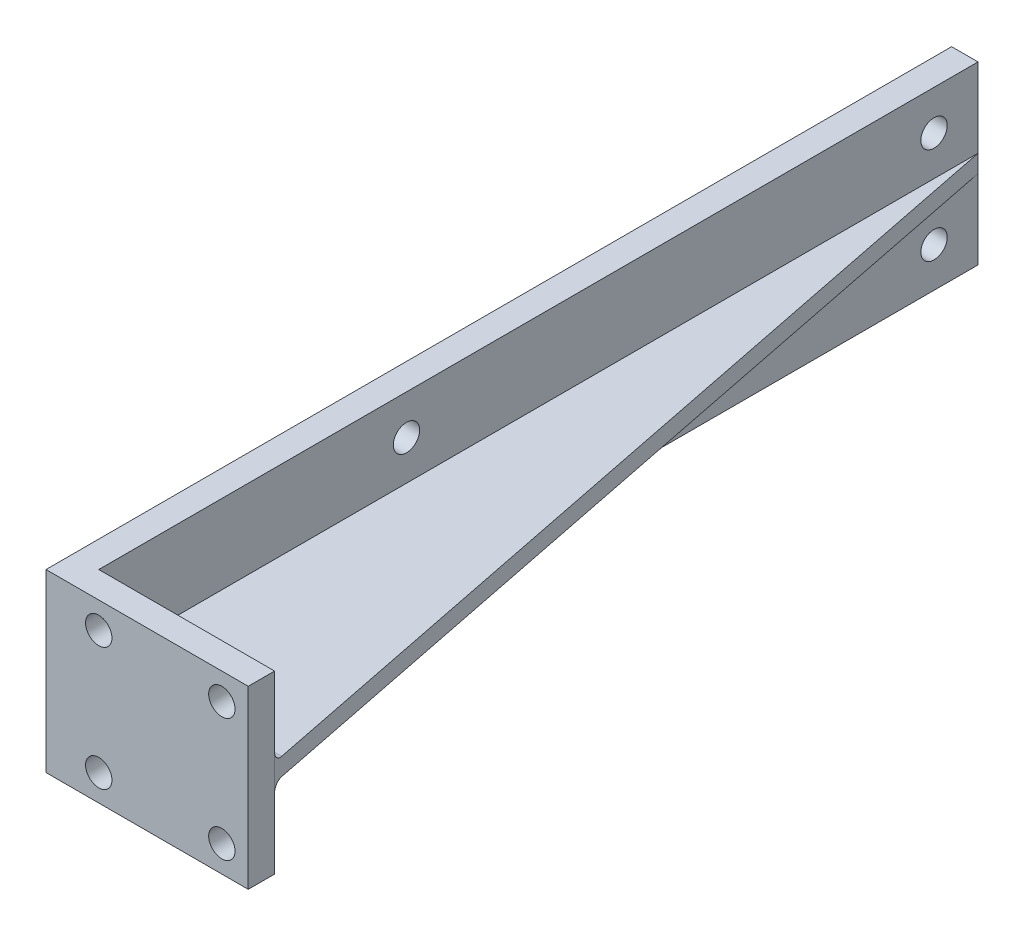
SolidWorks part; units mm, degrees
material "6061 合金"
ref_plane "前视基准面" through (0, 0, 0) normal (0, 0, 1) x (1, 0, 0)
ref_plane "上视基准面" through (0, 0, 0) normal (0, 1, 0) x (1, 0, 0)
ref_plane "右视基准面" through (0, 0, 0) normal (1, 0, 0) x (0, 0, -1)
sketch "草图1" plane through (0, 0, 0) normal (0, 1, 0) x (1, 0, 0)
  line L0 (0, 100) -> (0, 0)
  line L1 (0, 0) -> (20, 0)
  line L2 (20, 0) -> (0, 100)
  dimension "D1" = 100
  dimension "D2" = 20
extrude "凸台-拉伸1" add sketch "草图1" along normal blind 2
ref_plane "基准面1" through (0, 1, 0) normal (0, -1, 0) x (-1, 0, 0)
sketch "草图2" plane through (0, 1, 0) normal (0, -1, 0) x (-1, 0, 0)
  line L0 (-20, 0) -> (-20, -3)
  line L1 (-20, -3) -> (3, -3)
  line L2 (0, 100) -> (3, 100)
  line L3 (3, 100) -> (3, -3)
  line L4 (-20, 0) -> (0, 0)
  line L5 (0, 0) -> (0, 100)
  dimension "D1" = 3
  dimension "D2" = 3
extrude "凸台-拉伸2" add sketch "草图2" along normal blind 10 and the other way blind 10
sketch "草图3" plane through (0, 0, 0) normal (1, 0, 0) x (0, 0, -1)
  line L0 (100, 6.5) -> (0, 6.5) construction
  line L1 (100, 11) -> (100, 2) construction
  line L2 (0, 11) -> (0, 2) construction
  line L3 (100, 1) -> (0, 1) construction
  line L4 (100, 2) -> (100, 0) construction
  line L5 (0, 2) -> (0, 0) construction
  circle A0 centre (95, 6.5) radius 1.5
  circle A1 centre (35, 6.5) radius 1.5
  circle A2 centre (95, -4.5) radius 1.5
  circle A3 centre (35, -4.5) radius 1.5
  dimension "D1" = 3
  dimension "D2" = 5
  dimension "D3" = 60
extrude "切除-拉伸1" cut sketch "草图3" against normal through all
sketch "草图4" plane through (0, 0, 0) normal (0, 0, -1) x (-1, 0, 0)
  line L0 (-20, 1) -> (3, 1) construction
  line L1 (-20, 2) -> (-20, 0) construction
  line L2 (3, 11) -> (3, -9) construction
  line L4 (-10, 11) -> (-10, -9) construction
  line L5 (0, 11) -> (-20, 11) construction
  line L6 (0, -9) -> (-20, -9) construction
  circle A0 centre (-17, 8) radius 1.5
  circle A1 centre (-17, -6) radius 1.5
  circle A2 centre (-3, -6) radius 1.5
  circle A3 centre (-3, 8) radius 1.5
  dimension "D1" = 3
  dimension "D2" = 14
  dimension "D3" = 14
extrude "切除-拉伸2" cut sketch "草图4" against normal through all
fillet "圆角1" radius 1 2 edges at (10, 2, 0) (10, 0, 0)
